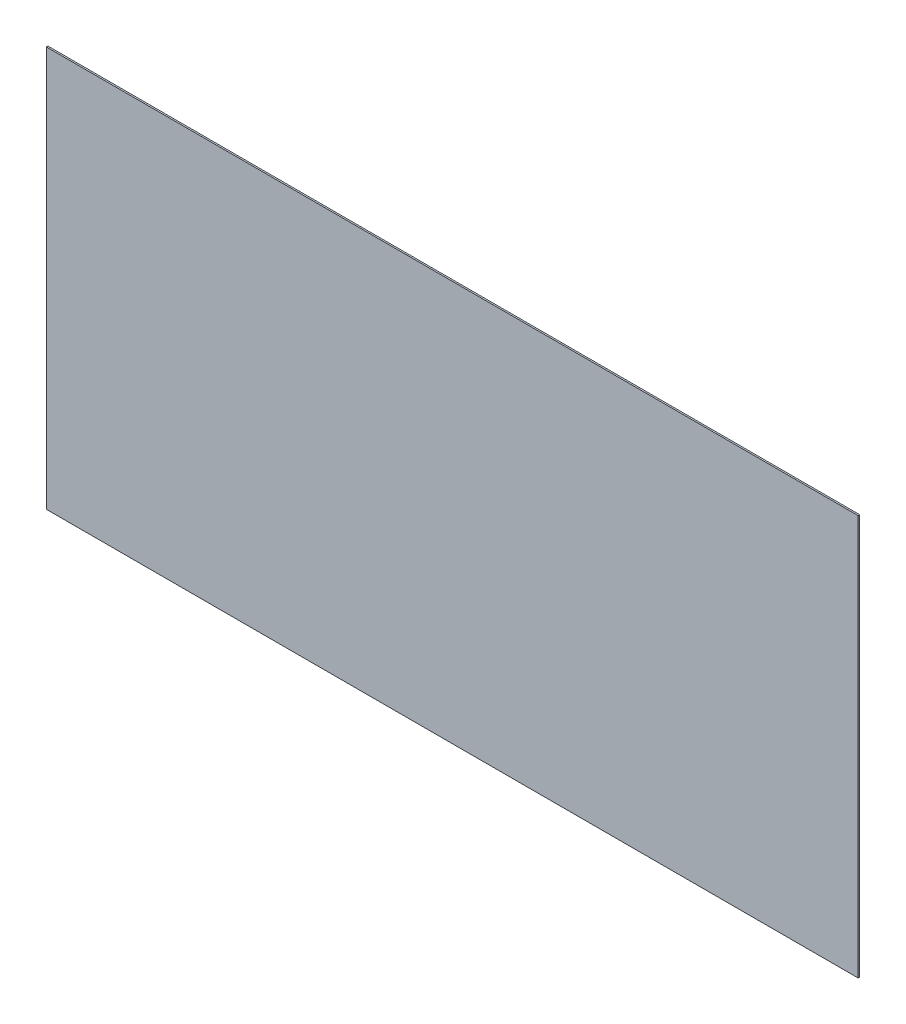
SolidWorks part; units mm, degrees
material "Oak"
ref_plane "Front Plane" through (0, 0, 0) normal (0, 0, 1) x (1, 0, 0)
ref_plane "Top Plane" through (0, 0, 0) normal (0, 1, 0) x (1, 0, 0)
ref_plane "Right Plane" through (0, 0, 0) normal (1, 0, 0) x (0, 0, -1)
sketch "Sketch1" plane through (0, 0, 0) normal (0, 0, 1) x (1, 0, 0)
  line L0 (0, 0) -> (259.5, 0)
  line L1 (259.5, 0) -> (259.5, 128)
  line L2 (259.5, 128) -> (0, 128)
  line L3 (0, 128) -> (0, 0)
  dimension "D1" = 259.5
  dimension "D2" = 128
extrude "Boss-Extrude1" add sketch "Sketch1" along normal blind 0.5
